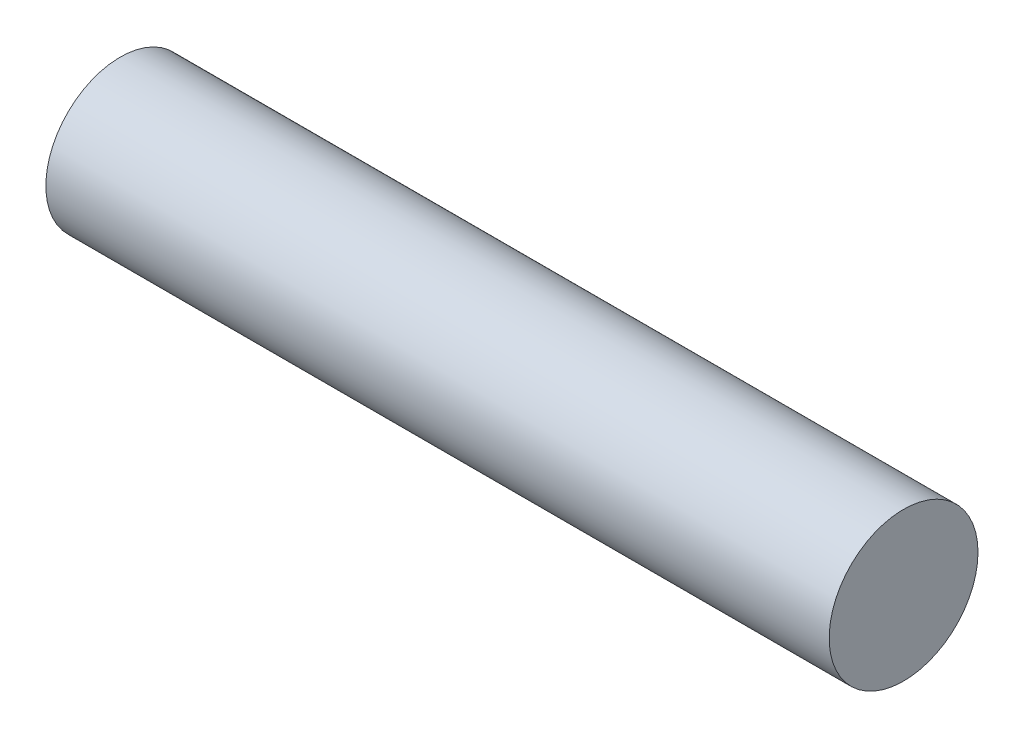
SolidWorks part; units mm, degrees
other "Preload Guide Rod"
ref_plane "Front Plane" through (0, 0, 0) normal (0, 0, 1) x (1, 0, 0)
ref_plane "Top Plane" through (0, 0, 0) normal (0, 1, 0) x (1, 0, 0)
ref_plane "Right Plane" through (0, 0, 0) normal (1, 0, 0) x (0, 0, -1)
sketch3d "Ground guide rod sketch datum points"
  point P0 (15.9, -9, -28)
  point P1 (15.9, 1, -28)
  point P2 (15.9, -9, -18)
ref_plane "Ground guide rod sketch plane" through (15.9, 0, 0) normal (1, 0, 0) x (0, 0, -1)
sketch "Ground guide rod sketch" plane through (15.9, 0, 0) normal (1, 0, 0) x (0, 0, -1)
  circle A0 centre (28, -9) radius 4
extrude "Ground guide rod" add sketch "Ground guide rod sketch" along normal blind 42.1 separate body
